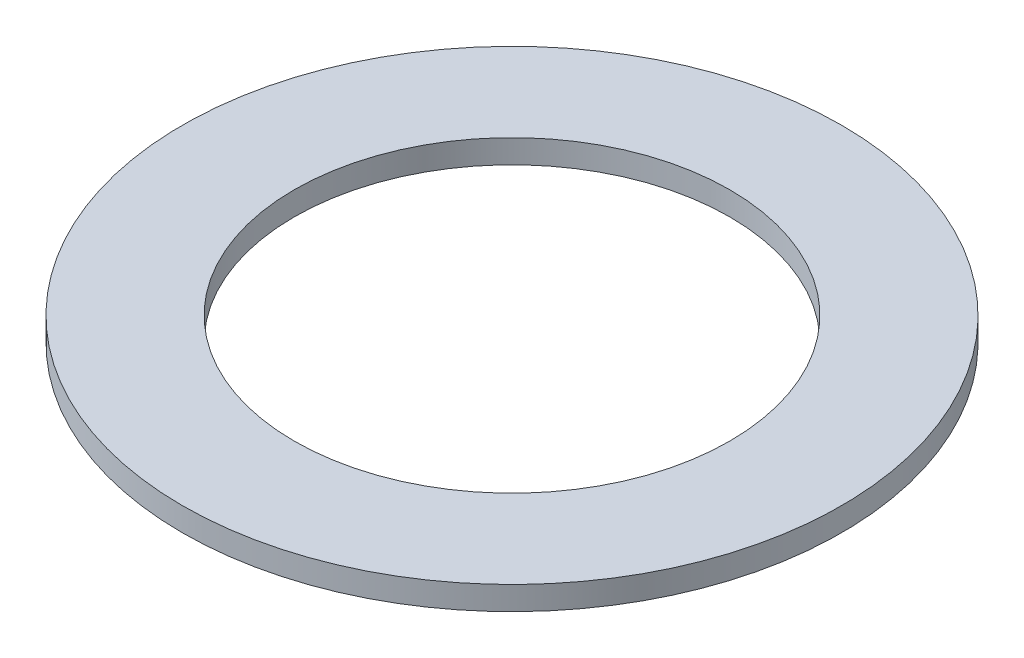
SolidWorks part; units mm, degrees
ref_plane "前视基准面" through (0, 0, 0) normal (0, 0, 1) x (1, 0, 0)
ref_plane "上视基准面" through (0, 0, 0) normal (0, 1, 0) x (1, 0, 0)
ref_plane "右视基准面" through (0, 0, 0) normal (1, 0, 0) x (0, 0, -1)
sketch "草图1" plane through (0, 0, 0) normal (0, 1, 0) x (1, 0, 0)
  circle A0 centre (0, 0) radius 18.5
  circle A1 centre (0, 0) radius 28
  dimension "D1" = 37
  dimension "D2" = 56
extrude "凸台-拉伸1" add sketch "草图1" along normal blind 2
